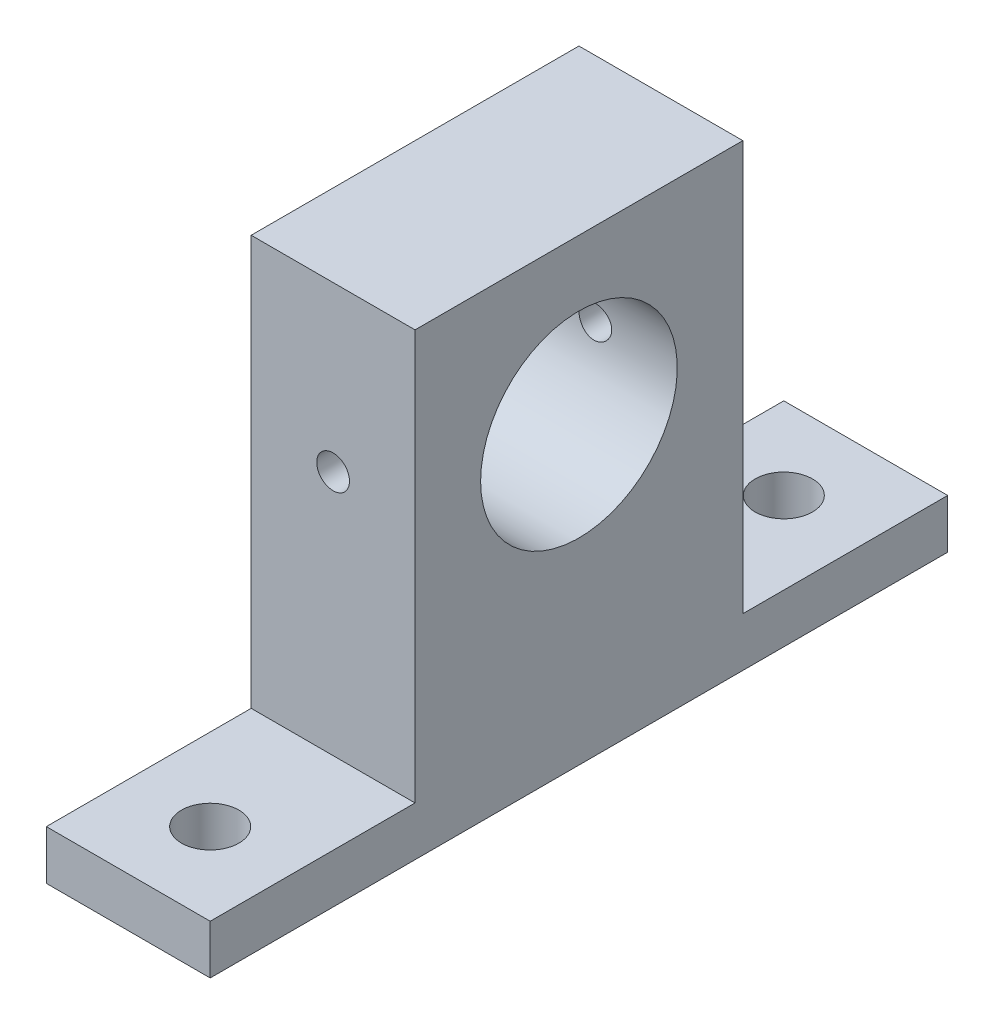
SolidWorks part; units mm, degrees
ref_plane "Front Plane" through (0, 0, 0) normal (0, 0, 1) x (1, 0, 0)
ref_plane "Top Plane" through (0, 0, 0) normal (0, 1, 0) x (1, 0, 0)
ref_plane "Right Plane" through (0, 0, 0) normal (1, 0, 0) x (0, 0, -1)
sketch "Sketch2" plane through (0, 0, 0) normal (0, 1, 0) x (1, 0, 0)
  line L0 (0, -55) -> (0, 55) construction
  line L1 (-5, 22.5) -> (5, 22.5)
  line L2 (-5, 22.5) -> (-5, -22.5)
  line L3 (-5, -22.5) -> (5, -22.5)
  line L4 (5, 22.5) -> (5, -22.5)
  line L5 (-5, 22.5) -> (5, -22.5) construction
  line L6 (-5, -22.5) -> (5, 22.5) construction
  circle A0 centre (0, 17.5) radius 1.75
  circle A1 centre (0, -17.5) radius 1.75
  point P0 (0, 0)
  dimension "D3" = 3.5
  dimension "D1" = 10
  dimension "D2" = 45
  dimension "D4" = 5
  dimension "D5" = 2
extrude "Boss-Extrude1" add sketch "Sketch2" along normal blind 3
sketch "Sketch3" plane through (0, 3, 0) normal (0, 1, 0) x (1, 0, 0)
  line L0 (5, -22.5) -> (5, 22.5) construction
  line L1 (-5, 10) -> (5, 10)
  line L2 (-5, 10) -> (-5, -10)
  line L3 (-5, -10) -> (5, -10)
  line L4 (5, 10) -> (5, -10)
  line L5 (-5, 10) -> (5, -10) construction
  line L6 (-5, -10) -> (5, 10) construction
  point P0 (0, 0)
  dimension "D1" = 20
extrude "Boss-Extrude2" add sketch "Sketch3" along normal blind 25
sketch "Sketch4" plane through (-5, 0, 0) normal (-1, 0, 0) x (0, 0, 1)
  line L0 (0, -1.65) -> (0, 1.65) construction
  line L1 (-10, 28) -> (10, 28) construction
  circle A0 centre (0, 18) radius 6
  dimension "D1" = 12
  dimension "D2" = 10
extrude "Cut-Extrude1" cut sketch "Sketch4" against normal blind 10
sketch "Sketch5" plane through (0, 0, 10) normal (0, 0, 1) x (1, 0, 0)
  line L0 (0, -1.65) -> (0, 1.65) construction
  line L1 (-5, 28) -> (5, 28) construction
  circle A0 centre (0, 18) radius 1
  point P4 (0, 0)
  point P5 (0, 0)
  dimension "D1" = 2
  dimension "D2" = 10
extrude "Cut-Extrude2" cut sketch "Sketch5" against normal blind 20
